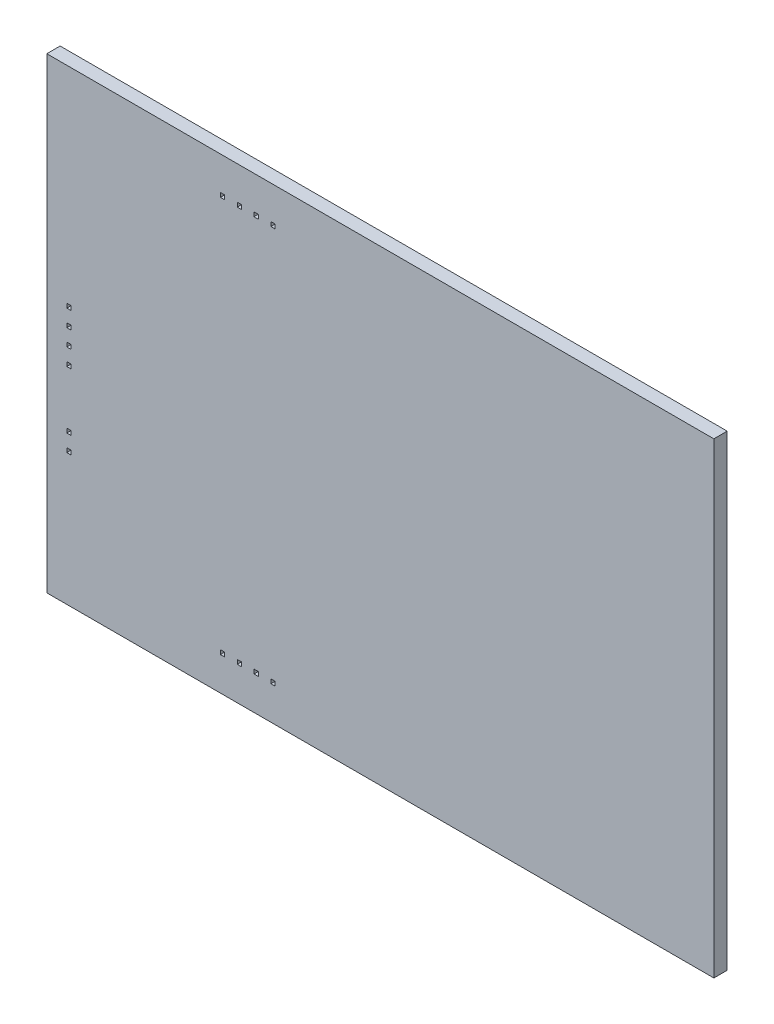
SolidWorks part; units mm, degrees
ref_plane "Alzado" through (0, 0, 0) normal (0, 0, 1) x (1, 0, 0)
ref_plane "Planta" through (0, 0, 0) normal (0, 1, 0) x (1, 0, 0)
ref_plane "Vista lateral" through (0, 0, 0) normal (1, 0, 0) x (0, 0, -1)
sketch "Croquis1" plane through (0, 0, 0) normal (0, 0, 1) x (1, 0, 0)
  line L1 (0, 0) -> (130, 0)
  line L2 (0, 0) -> (0, 70)
  line L3 (0, 70) -> (130, 70)
  line L4 (130, 0) -> (130, 70)
  dimension "D1" = 70
  dimension "D2" = 130
extrude "Saliente-Extruir1" add sketch "Croquis1" along normal blind 2
sketch "Croquis2" plane through (0, 0, 0) normal (0, 0, -1) x (-1, 0, 0)
  line L2 (-130, 70) -> (0, 70) construction
  line L3 (-130, 0) -> (-100, 0)
  line L4 (-130, 0) -> (-130, 70)
  line L5 (-130, 70) -> (-100, 70)
  line L6 (-100, 0) -> (-100, 70)
  dimension "D1" = 30
extrude "Cortar-Extruir1" cut sketch "Croquis2" against normal through all
sketch "Croquis3" plane through (0, 0, 0) normal (0, 0, -1) x (-1, 0, 0)
  line L0 (0, 0) -> (-30.13, 0) construction
  line L1 (-30.13, 0) -> (-30.13, 5.32) construction
  line L2 (0, 0) -> (0, 35) construction
  line L3 (0, 70) -> (0, 0) construction
  line L4 (0, 35) -> (-2.5, 35) construction
  line L5 (-2.5, 35) -> (-2.5, 35.93) construction
  line L6 (-2.5, 35.93) -> (-3, 35.93) construction
  line L7 (-3.32, 36.57) -> (-3.32, 38.47) construction
  line L8 (-3, 35.93) -> (-3.64, 35.93)
  line L9 (-3, 35.93) -> (-3, 36.57)
  line L10 (-3, 36.57) -> (-3.64, 36.57)
  line L11 (-3.64, 35.93) -> (-3.64, 36.57)
  line L12 (-3.32, 38.47) -> (-3, 38.47) construction
  line L13 (-3, 31.53) -> (-3, 30.89)
  line L14 (-3, 38.47) -> (-3.64, 38.47)
  line L15 (-3, 38.47) -> (-3, 39.11)
  line L16 (-3, 39.11) -> (-3.64, 39.11)
  line L17 (-3.64, 38.47) -> (-3.64, 39.11)
  line L18 (-3, 30.89) -> (-3.64, 30.89)
  line L19 (-3.64, 31.53) -> (-3.64, 30.89)
  line L20 (-3, 31.53) -> (-3.64, 31.53)
  line L21 (-3, 33.43) -> (-3.64, 33.43)
  line L22 (-3, 34.07) -> (-3, 33.43)
  line L23 (-3, 34.07) -> (-3.64, 34.07)
  line L24 (-3.64, 34.07) -> (-3.64, 33.43)
  line L25 (-3.32, 30.89) -> (-3.32, 26.89) construction
  line L26 (0, 70) -> (0, 0) construction
  line L27 (-30.13, 5.32) -> (-29.2, 5.32) construction
  line L28 (-29.2, 5.32) -> (-29.2, 5) construction
  line L29 (-28.56, 5.32) -> (-26.66, 5.32) construction
  line L30 (-29.2, 5) -> (-28.56, 5)
  line L31 (-29.2, 5) -> (-29.2, 5.64)
  line L32 (-29.2, 5.64) -> (-28.56, 5.64)
  line L33 (-28.56, 5) -> (-28.56, 5.64)
  line L34 (-34.24, 5) -> (-34.24, 5.64)
  line L35 (-26.66, 5) -> (-26.02, 5)
  line L36 (-26.66, 5) -> (-26.66, 5.64)
  line L37 (-26.66, 5.64) -> (-26.02, 5.64)
  line L38 (-26.02, 5) -> (-26.02, 5.64)
  line L39 (-33.6, 5.64) -> (-34.24, 5.64)
  line L40 (-33.6, 5) -> (-34.24, 5)
  line L41 (-33.6, 5) -> (-33.6, 5.64)
  line L42 (-31.7, 5) -> (-31.7, 5.64)
  line L43 (-31.06, 5) -> (-31.7, 5)
  line L44 (-31.06, 5.64) -> (-31.7, 5.64)
  line L45 (-31.06, 5) -> (-31.06, 5.64)
  line L46 (-33.6, 65) -> (-34.24, 65)
  line L47 (-33.6, 65) -> (-33.6, 64.36)
  line L48 (-33.6, 64.36) -> (-34.24, 64.36)
  line L49 (-34.24, 65) -> (-34.24, 64.36)
  line L50 (-31.06, 65) -> (-31.7, 65)
  line L51 (-31.06, 65) -> (-31.06, 64.36)
  line L52 (-31.06, 64.36) -> (-31.7, 64.36)
  line L53 (-31.7, 65) -> (-31.7, 64.36)
  line L54 (-26.66, 64.36) -> (-26.02, 64.36)
  line L55 (-26.02, 65) -> (-26.02, 64.36)
  line L56 (-26.66, 65) -> (-26.02, 65)
  line L57 (-26.66, 65) -> (-26.66, 64.36)
  line L58 (-28.56, 65) -> (-28.56, 64.36)
  line L59 (-29.2, 65) -> (-28.56, 65)
  line L60 (-29.2, 65) -> (-29.2, 64.36)
  line L61 (-29.2, 64.36) -> (-28.56, 64.36)
  line L62 (-3.32, 26.89) -> (-3, 26.89) construction
  line L63 (-3, 19.71) -> (-3, 20.35)
  line L64 (-3, 19.71) -> (-3.64, 19.71)
  line L65 (-3.64, 19.71) -> (-3.64, 20.35)
  line L66 (-3, 20.35) -> (-3.64, 20.35)
  line L67 (-3, 22.25) -> (-3.64, 22.25)
  line L68 (-3.64, 22.25) -> (-3.64, 22.89)
  line L69 (-3, 22.89) -> (-3.64, 22.89)
  line L70 (-3, 22.25) -> (-3, 22.89)
  dimension "D1" = 0.64
  dimension "D2" = 0.64
  dimension "D3" = 0.64
  dimension "D4" = 0.64
  dimension "D5" = 3
  dimension "D6" = 0.93
  dimension "D7" = 1.9
  dimension "D8" = 3
  dimension "D9" = 2.5
  dimension "D10" = 0.64
  dimension "D11" = 0.64
  dimension "D12" = 0.64
  dimension "D13" = 0.64
  dimension "D14" = 1.9
  dimension "D15" = 5
  dimension "D16" = 5
  dimension "D17" = 26.02
  dimension "D18" = 30.13
  dimension "D19" = 4
  dimension "D20" = 8
extrude "Cortar-Extruir2" cut sketch "Croquis3" against normal through all
